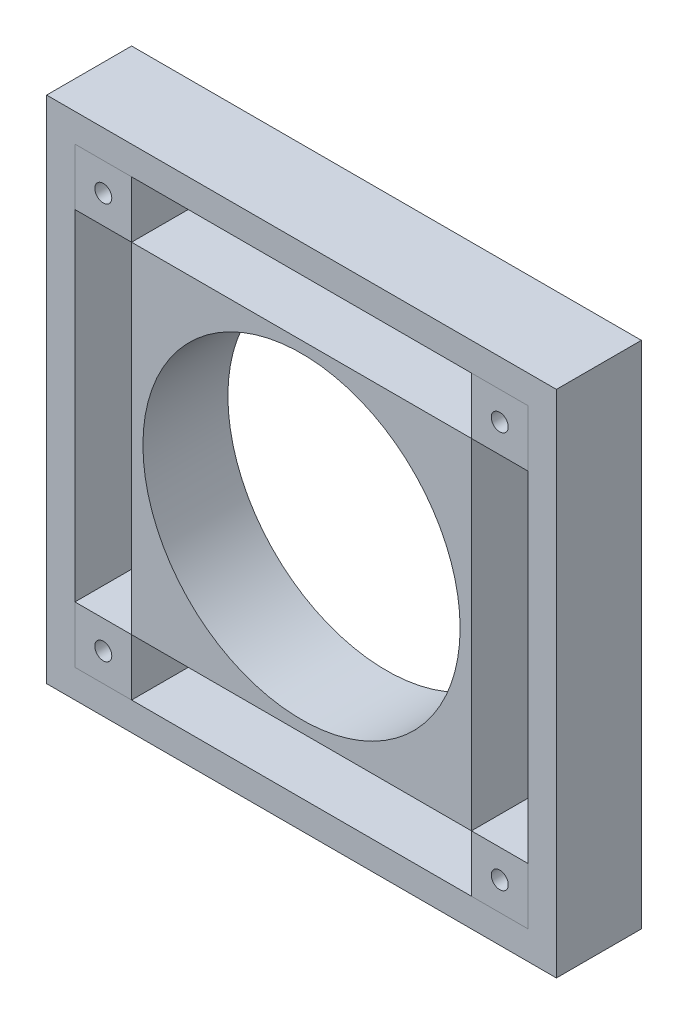
SolidWorks part; units mm, degrees
ref_plane "Front Plane" through (0, 0, 0) normal (0, 0, 1) x (1, 0, 0)
ref_plane "Top Plane" through (0, 0, 0) normal (0, 1, 0) x (1, 0, 0)
ref_plane "Right Plane" through (0, 0, 0) normal (1, 0, 0) x (0, 0, -1)
sketch "Sketch2" plane through (0, 0, 0) normal (0, 0, 1) x (1, 0, 0)
  line L1 (0, 0) -> (90, 0)
  line L2 (0, 0) -> (0, 90)
  line L3 (0, 90) -> (90, 90)
  line L4 (90, 0) -> (90, 90)
  dimension "D1" = 90
  dimension "D2" = 90
extrude "Boss-Extrude1" add sketch "Sketch2" along normal blind 15
sketch "Sketch3" plane through (0, 0, 15) normal (0, 0, 1) x (1, 0, 0)
  line L8 (5, 85) -> (5, 5)
  line L9 (5, 5) -> (85, 5)
  line L10 (85, 5) -> (85, 85)
  line L11 (85, 85) -> (5, 85)
  line L12 (5, 85) -> (5, 5)
  line L13 (5, 5) -> (85, 5)
  line L14 (85, 5) -> (85, 85)
  line L15 (85, 85) -> (5, 85)
  line L26 (15, 15) -> (75, 15)
  line L27 (75, 15) -> (75, 75)
  line L28 (75, 75) -> (15, 75)
  line L29 (15, 75) -> (15, 15)
  line L30 (15, 15) -> (75, 15)
  line L31 (75, 15) -> (75, 75)
  line L32 (75, 75) -> (15, 75)
  line L33 (15, 75) -> (15, 15)
  dimension "D1" = 5
  dimension "D2" = 15
extrude "Cut-Extrude1" cut sketch "Sketch3" against normal blind 10 contours L12 L13 L14 L15 | L30 L31 L32 L33
sketch "Sketch4" plane through (0, 0, 5) normal (0, 0, 1) x (1, 0, 0)
  line L0 (15, 75) -> (5, 75)
  line L1 (15, 75) -> (15, 85)
  line L2 (5, 75) -> (5, 85)
  line L3 (15, 85) -> (5, 85)
  line L4 (5, 85) -> (5, 5) construction
extrude "Boss-Extrude5" add sketch "Sketch4" along normal through all separate body
pattern_circular "CirPattern3" count 4 over 360 about axis through (45, 45, 0) along (0, 0, 1) of bodies 103
sketch "Sketch5" plane through (0, 0, 15) normal (0, 0, 1) x (1, 0, 0)
  line L0 (0, 45) -> (90, 45) construction
  line L1 (0, 90) -> (0, 0) construction
  line L2 (90, 0) -> (90, 90) construction
  line L3 (45, 90) -> (45, 0) construction
  line L4 (90, 90) -> (0, 90) construction
  line L5 (0, 0) -> (90, 0) construction
  line L18 (17, 73) -> (17, 17)
  line L19 (17, 17) -> (73, 17)
  line L20 (73, 17) -> (73, 73)
  line L21 (73, 73) -> (17, 73)
  line L22 (17, 73) -> (17, 17) construction
  line L23 (17, 17) -> (73, 17) construction
  line L24 (73, 17) -> (73, 73) construction
  line L25 (73, 73) -> (17, 73) construction
  circle A1 centre (45, 45) radius 28
  dimension "D1" = 2
extrude "Cut-Extrude2" cut sketch "Sketch5" against normal through all
sketch "Sketch6" plane through (0, 0, 15) normal (0, 0, 1) x (1, 0, 0)
  line L1 (10, 100.9112) -> (10, 63.2327) construction
  line L3 (-7.1806, 80) -> (25.1559, 80) construction
  line L4 (5, 85) -> (5, 75) construction
  line L5 (15, 85) -> (5, 85) construction
  circle A0 centre (10, 80) radius 1.5
  point P8 (5, 80)
  point P11 (10, 85)
  dimension "D1" = 3
extrude "Cut-Extrude3" cut sketch "Sketch6" against normal through all
sketch "Sketch7" plane through (0, 0, 0) normal (0, 0, 1) x (1, 0, 0)
  line L0 (45, 133.1974) -> (45, -29.564) construction
  line L1 (-68.727, 45) -> (185.3086, 45) construction
  line L2 (90, 0) -> (90, 90) construction
  line L3 (90, 90) -> (0, 90) construction
  circle A0 centre (45, 45) radius 1 construction
  point P6 (90, 45)
  point P9 (45, 90)
  dimension "D1" = 2
ref_plane "Plane1" through (45, 0, 0) normal (-1, 0, 0) x (0, 0, 1)
ref_plane "Plane2" through (0, 45, 0) normal (0, -1, 0) x (-1, 0, 0)
mirror "Mirror1" about plane through (0, 45, 0) normal (0, -1, 0) of "Cut-Extrude3"
mirror "Mirror2" about plane through (45, 0, 0) normal (-1, 0, 0) of "Mirror1", "Cut-Extrude3"
